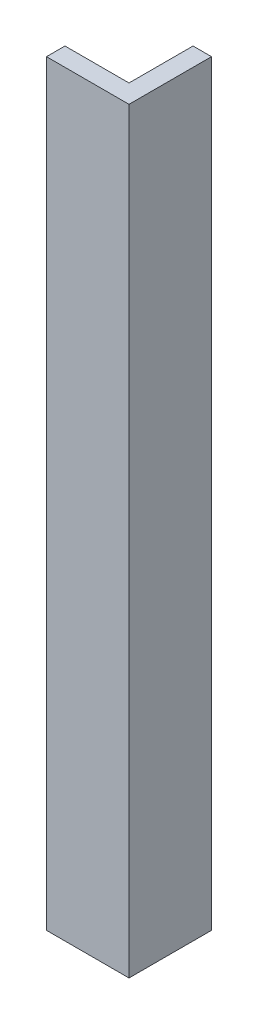
SolidWorks part; units mm, degrees
ref_plane "Front Plane" through (0, 0, 0) normal (0, 0, 1) x (1, 0, 0)
ref_plane "Top Plane" through (0, 0, 0) normal (0, 1, 0) x (1, 0, 0)
ref_plane "Right Plane" through (0, 0, 0) normal (1, 0, 0) x (0, 0, -1)
sketch "Sketch1" plane through (0, 0, 0) normal (0, 1, 0) x (1, 0, 0)
  line L1 (-3.175, 3.175) -> (-14.175, 3.175)
  line L2 (0, 14.175) -> (0, 0)
  line L3 (0, 0) -> (-14.175, 0)
  line L4 (-14.175, 3.175) -> (-14.175, 0)
  line L7 (0, 14.175) -> (-3.175, 14.175)
  line L8 (-3.175, 3.175) -> (-3.175, 14.175)
  dimension "D1" = 3.175
  dimension "D2" = 11
extrude "Boss-Extrude1" add sketch "Sketch1" along normal blind 130 contours L1 L4 L3 L2 L7 L8
